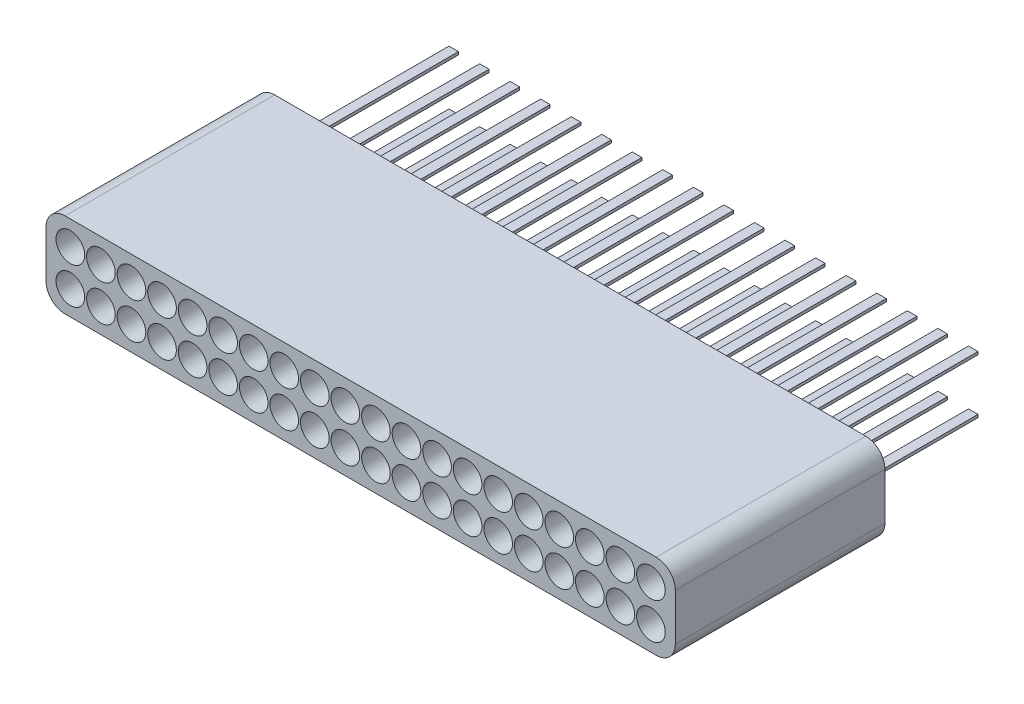
SolidWorks part; units mm, degrees
ref_plane "Front Plane" through (0, 0, 0) normal (0, 0, 1) x (1, 0, 0)
ref_plane "Top Plane" through (0, 0, 0) normal (0, 1, 0) x (1, 0, 0)
ref_plane "Right Plane" through (0, 0, 0) normal (1, 0, 0) x (0, 0, -1)
sketch "Sketch1" plane through (0, 0, 0) normal (0, 0, 1) x (1, 0, 0)
  line L5 (6.59, 0.89) -> (-6.59, 0.89)
  line L6 (6.59, 0.89) -> (6.59, -0.89)
  line L7 (6.59, -0.89) -> (-6.59, -0.89)
  line L8 (-6.59, 0.89) -> (-6.59, -0.89)
  line L9 (6.59, 0.89) -> (-6.59, -0.89) construction
  line L10 (6.59, -0.89) -> (-6.59, 0.89) construction
  point P0 (0, 0)
  dimension "D1" = 1.78
  dimension "D2" = 13.18
extrude "Boss-Extrude1" add sketch "Sketch1" along normal blind 4.39
sketch "Sketch2" plane through (0, 0, 0) normal (0, 0, 1) x (1, 0, 0)
  line L0 (6.59, -0.89) -> (6.59, 0.89) construction
  line L1 (5.54, 0.6) -> (5.34, 0.6)
  line L2 (5.54, 0.6) -> (5.54, 0.54)
  line L3 (5.54, 0.54) -> (5.34, 0.54)
  line L4 (5.34, 0.6) -> (5.34, 0.54)
  line L5 (5.54, 0.6) -> (5.34, 0.54) construction
  line L6 (5.54, 0.54) -> (5.34, 0.6) construction
  point P0 (5.44, 0.57)
  point P7 (6.59, 0)
  dimension "D1" = 0.2
  dimension "D2" = 0.06
  dimension "D3" = 1.15
  dimension "D4" = 0.57
extrude "Boss-Extrude2" add sketch "Sketch2" against normal blind 3
pattern_linear "LPattern2" count 18 spacing 0.64 along (-1, 0, 0) count 2 spacing 1.14 along (0, -1, 0) of "Boss-Extrude2"
sketch "Sketch3" plane through (0, 0, 4.39) normal (0, 0, 1) x (1, 0, 0)
  line L2 (6.59, -0.89) -> (6.59, 0.89) construction
  circle A1 centre (6.08, -0.38) radius 0.3
  point P7 (6.59, 0)
  point P11 (6.08, -0.115)
  dimension "D1" = 0.6
  dimension "D3" = 0.38
  dimension "D2" = 0.51
extrude "Cut-Extrude1" cut sketch "Sketch3" against normal blind 3 contours A1
pattern_linear "LPattern1" count 20 spacing 0.64 along (-1, 0, 0) count 2 spacing 0.76 along (0, 1, 0) of "Cut-Extrude1"
fillet "Fillet1" radius 0.4 4 edges at (6.59, 0.89, 2.195) (6.59, -0.89, 2.195) (-6.59, -0.89, 2.195) (-6.59, 0.89, 2.195)
